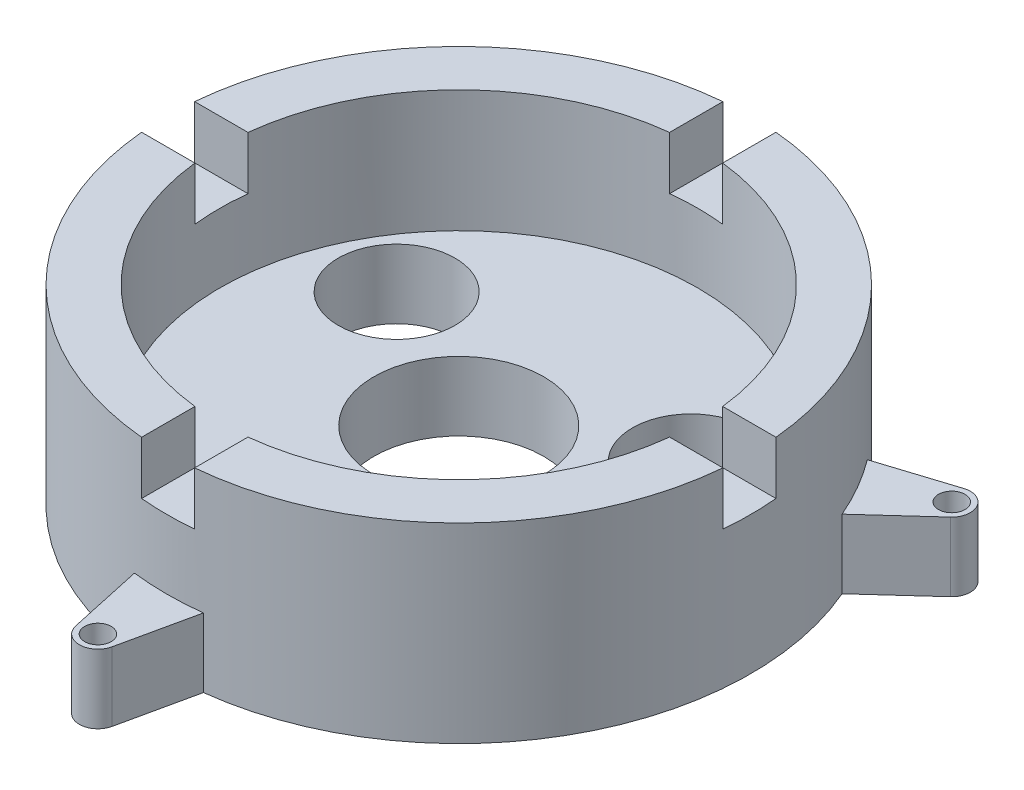
SolidWorks part; units mm, degrees
ref_plane "Front Plane" through (0, 0, 0) normal (0, 0, 1) x (1, 0, 0)
ref_plane "Top Plane" through (0, 0, 0) normal (0, 1, 0) x (1, 0, 0)
ref_plane "Right Plane" through (0, 0, 0) normal (1, 0, 0) x (0, 0, -1)
sketch "Sketch1" plane through (0, 0, 0) normal (0, 0, 1) x (1, 0, 0)
  line L0 (16, 0) -> (16, 13)
  line L1 (16, 13) -> (45, 13)
  line L2 (45, 13) -> (45, 36)
  line L3 (45, 36) -> (55, 36)
  line L4 (55, 36) -> (55, 0)
  line L5 (55, 0) -> (16, 0)
  line L6 (0, 0) -> (0, 61.1098) construction
  dimension "D1" = 32
  dimension "D2" = 55
  dimension "D3" = 45
  dimension "D4" = 13
  dimension "D5" = 36
revolve "Revolve2" add sketch "Sketch1" angle 360 about L6
sketch "Sketch2" plane through (0, 36, 0) normal (0, 1, 0) x (1, 0, 0)
  line L0 (0, 0) -> (78.522, 0) construction
  line L1 (44.7214, 5) -> (54.7723, 5)
  line L2 (44.7214, -5) -> (54.7723, -5)
  circle A0 centre (0, 0) radius 55 construction
  circle A1 centre (0, 0) radius 45 construction
  arc A2 (54.7723, -5) -> (54.7723, 5) centre (0, 0) ccw
  arc A3 (44.7214, -5) -> (44.7214, 5) centre (0, 0) ccw
  dimension "D1" = 10
extrude "Cut-Extrude1" cut sketch "Sketch2" against normal blind 10
pattern_circular "CirPattern1" count 4 over 360 about axis through (0, 0, 0) along (0, 1, 0) of "Cut-Extrude1"
sketch "Sketch3" plane through (0, 13, 0) normal (0, 1, 0) x (1, 0, 0)
  circle A0 centre (0, -32) radius 11
  point P2 (0, -32.0216)
  dimension "D1" = 22
  dimension "D2" = 32
extrude "Cut-Extrude2" cut sketch "Sketch3" against normal through all
pattern_circular "CirPattern2" count 3 over 360 about axis through (0, 0, 0) along (0, 1, 0) of "Cut-Extrude2"
sketch "Sketch5" plane through (0, 0, 0) normal (0, -1, 0) x (1, 0, 0)
  line L0 (0, 0) -> (0, 68.4837) construction
  line L1 (-6.5, 54.6146) -> (-3.4197, 68.7454)
  line L2 (6.5, 54.6146) -> (3.4197, 68.7454)
  circle A0 centre (0, 0) radius 55 construction
  arc A1 (6.5, 54.6146) -> (-6.5, 54.6146) centre (0, 0) ccw
  arc A2 (3.4197, 68.7454) -> (-3.4197, 68.7454) centre (0, 68) ccw
  circle A3 centre (0, 68) radius 2.5
  dimension "D1" = 7
  dimension "D2" = 5
  dimension "D3" = 13
  dimension "D4" = 68
extrude "Boss-Extrude1" add sketch "Sketch5" against normal blind 13
pattern_circular "CirPattern3" count 3 over 360 about axis through (0, 0, 0) along (0, 1, 0) of "Boss-Extrude1"
